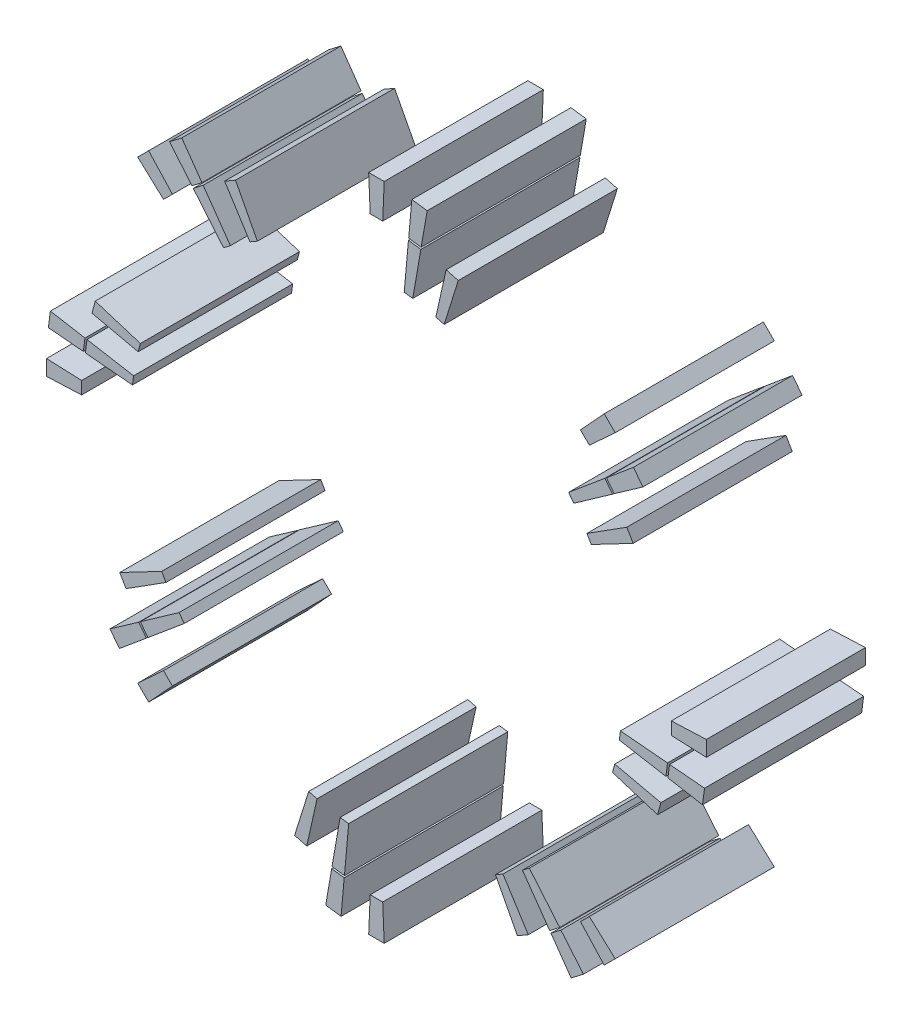
SolidWorks part; units mm, degrees
ref_plane "Спереди" through (0, 0, 0) normal (0, 0, 1) x (1, 0, 0)
ref_plane "Сверху" through (0, 0, 0) normal (0, 1, 0) x (1, 0, 0)
ref_plane "Справа" through (0, 0, 0) normal (1, 0, 0) x (0, 0, -1)
sketch "Эскиз1" plane through (0, 0, 0) normal (0, 0, 1) x (1, 0, 0)
  line L0 (55.5874, -1.1828) -> (62.2, -1.4625)
  line L1 (62.2, -1.4625) -> (62.2, 1.4625)
  line L2 (62.2, 1.4625) -> (55.5874, 1.1828)
  line L3 (55.5874, 1.1828) -> (55.5874, -1.1828)
  line L4 (40.4971, 22.4428) -> (48.396, 26.5757)
  line L5 (48.396, 26.5757) -> (47.2132, 28.6243)
  line L6 (47.2132, 28.6243) -> (39.6846, 23.8501)
  line L7 (39.6846, 23.8501) -> (40.4971, 22.4428)
  line L8 (44.8205, 32.9011) -> (50.2369, 36.7047)
  line L9 (50.2369, 36.7047) -> (48.4563, 39.0252)
  line L10 (48.4563, 39.0252) -> (43.3804, 34.7779)
  line L11 (43.3804, 34.7779) -> (44.8205, 32.9011)
  line L12 (37.2212, 27.5367) -> (44.5131, 32.6653)
  line L13 (44.5131, 32.6653) -> (43.0731, 34.542)
  line L14 (43.0731, 34.542) -> (36.232, 28.8259)
  line L15 (36.232, 28.8259) -> (37.2212, 27.5367)
  line L16 (40.1426, 38.4699) -> (45.0162, 42.9479)
  line L17 (45.0162, 42.9479) -> (42.9479, 45.0162)
  line L18 (42.9479, 45.0162) -> (38.4699, 40.1426)
  line L19 (38.4699, 40.1426) -> (40.1426, 38.4699)
  line L20 (12.7663, 44.5052) -> (15.4293, 53.013)
  line L21 (15.4293, 53.013) -> (13.1443, 53.6252)
  line L22 (13.1443, 53.6252) -> (11.1967, 44.9258)
  line L23 (11.1967, 44.9258) -> (12.7663, 44.5052)
  line L24 (8.4283, 54.9575) -> (9.5687, 61.477)
  line L25 (9.5687, 61.477) -> (6.6687, 61.8588)
  line L26 (6.6687, 61.8588) -> (6.0829, 55.2662)
  line L27 (6.0829, 55.2662) -> (8.4283, 54.9575)
  line L28 (6.848, 45.7908) -> (8.3777, 54.5734)
  line L29 (8.3777, 54.5734) -> (6.0324, 54.8821)
  line L30 (6.0324, 54.8821) -> (5.2369, 46.0029)
  line L31 (5.2369, 46.0029) -> (6.848, 45.7908)
  line L32 (1.1828, 55.5874) -> (1.4625, 62.2)
  line L33 (1.4625, 62.2) -> (-1.4625, 62.2)
  line L34 (-1.4625, 62.2) -> (-1.1828, 55.5874)
  line L35 (-1.1828, 55.5874) -> (1.1828, 55.5874)
  line L36 (-22.4428, 40.4971) -> (-26.5757, 48.396)
  line L37 (-26.5757, 48.396) -> (-28.6243, 47.2132)
  line L38 (-28.6243, 47.2132) -> (-23.8501, 39.6846)
  line L39 (-23.8501, 39.6846) -> (-22.4428, 40.4971)
  line L40 (-32.9011, 44.8205) -> (-36.7047, 50.2369)
  line L41 (-36.7047, 50.2369) -> (-39.0252, 48.4563)
  line L42 (-39.0252, 48.4563) -> (-34.7779, 43.3804)
  line L43 (-34.7779, 43.3804) -> (-32.9011, 44.8205)
  line L44 (-27.5367, 37.2212) -> (-32.6653, 44.5131)
  line L45 (-32.6653, 44.5131) -> (-34.542, 43.0731)
  line L46 (-34.542, 43.0731) -> (-28.8259, 36.232)
  line L47 (-28.8259, 36.232) -> (-27.5367, 37.2212)
  line L48 (-38.4699, 40.1426) -> (-42.9479, 45.0162)
  line L49 (-42.9479, 45.0162) -> (-45.0162, 42.9479)
  line L50 (-45.0162, 42.9479) -> (-40.1426, 38.4699)
  line L51 (-40.1426, 38.4699) -> (-38.4699, 40.1426)
  line L52 (-44.5052, 12.7663) -> (-53.013, 15.4293)
  line L53 (-53.013, 15.4293) -> (-53.6252, 13.1443)
  line L54 (-53.6252, 13.1443) -> (-44.9258, 11.1967)
  line L55 (-44.9258, 11.1967) -> (-44.5052, 12.7663)
  line L56 (-54.9575, 8.4283) -> (-61.477, 9.5687)
  line L57 (-61.477, 9.5687) -> (-61.8588, 6.6687)
  line L58 (-61.8588, 6.6687) -> (-55.2662, 6.0829)
  line L59 (-55.2662, 6.0829) -> (-54.9575, 8.4283)
  line L60 (-45.7908, 6.848) -> (-54.5734, 8.3777)
  line L61 (-54.5734, 8.3777) -> (-54.8821, 6.0324)
  line L62 (-54.8821, 6.0324) -> (-46.0029, 5.2369)
  line L63 (-46.0029, 5.2369) -> (-45.7908, 6.848)
  line L64 (-55.5874, 1.1828) -> (-62.2, 1.4625)
  line L65 (-62.2, 1.4625) -> (-62.2, -1.4625)
  line L66 (-62.2, -1.4625) -> (-55.5874, -1.1828)
  line L67 (-55.5874, -1.1828) -> (-55.5874, 1.1828)
  line L68 (-40.4971, -22.4428) -> (-48.396, -26.5757)
  line L69 (-48.396, -26.5757) -> (-47.2132, -28.6243)
  line L70 (-47.2132, -28.6243) -> (-39.6846, -23.8501)
  line L71 (-39.6846, -23.8501) -> (-40.4971, -22.4428)
  line L72 (-44.8205, -32.9011) -> (-50.2369, -36.7047)
  line L73 (-50.2369, -36.7047) -> (-48.4563, -39.0252)
  line L74 (-48.4563, -39.0252) -> (-43.3804, -34.7779)
  line L75 (-43.3804, -34.7779) -> (-44.8205, -32.9011)
  line L76 (-37.2212, -27.5367) -> (-44.5131, -32.6653)
  line L77 (-44.5131, -32.6653) -> (-43.0731, -34.542)
  line L78 (-43.0731, -34.542) -> (-36.232, -28.8259)
  line L79 (-36.232, -28.8259) -> (-37.2212, -27.5367)
  line L80 (-40.1426, -38.4699) -> (-45.0162, -42.9479)
  line L81 (-45.0162, -42.9479) -> (-42.9479, -45.0162)
  line L82 (-42.9479, -45.0162) -> (-38.4699, -40.1426)
  line L83 (-38.4699, -40.1426) -> (-40.1426, -38.4699)
  line L84 (-12.7663, -44.5052) -> (-15.4293, -53.013)
  line L85 (-15.4293, -53.013) -> (-13.1443, -53.6252)
  line L86 (-13.1443, -53.6252) -> (-11.1967, -44.9258)
  line L87 (-11.1967, -44.9258) -> (-12.7663, -44.5052)
  line L88 (-8.4283, -54.9575) -> (-9.5687, -61.477)
  line L89 (-9.5687, -61.477) -> (-6.6687, -61.8588)
  line L90 (-6.6687, -61.8588) -> (-6.0829, -55.2662)
  line L91 (-6.0829, -55.2662) -> (-8.4283, -54.9575)
  line L92 (-6.848, -45.7908) -> (-8.3777, -54.5734)
  line L93 (-8.3777, -54.5734) -> (-6.0324, -54.8821)
  line L94 (-6.0324, -54.8821) -> (-5.2369, -46.0029)
  line L95 (-5.2369, -46.0029) -> (-6.848, -45.7908)
  line L96 (-1.1828, -55.5874) -> (-1.4625, -62.2)
  line L97 (-1.4625, -62.2) -> (1.4625, -62.2)
  line L98 (1.4625, -62.2) -> (1.1828, -55.5874)
  line L99 (1.1828, -55.5874) -> (-1.1828, -55.5874)
  line L100 (22.4428, -40.4971) -> (26.5757, -48.396)
  line L101 (26.5757, -48.396) -> (28.6243, -47.2132)
  line L102 (28.6243, -47.2132) -> (23.8501, -39.6846)
  line L103 (23.8501, -39.6846) -> (22.4428, -40.4971)
  line L104 (32.9011, -44.8205) -> (36.7047, -50.2369)
  line L105 (36.7047, -50.2369) -> (39.0252, -48.4563)
  line L106 (39.0252, -48.4563) -> (34.7779, -43.3804)
  line L107 (34.7779, -43.3804) -> (32.9011, -44.8205)
  line L108 (27.5367, -37.2212) -> (32.6653, -44.5131)
  line L109 (32.6653, -44.5131) -> (34.542, -43.0731)
  line L110 (34.542, -43.0731) -> (28.8259, -36.232)
  line L111 (28.8259, -36.232) -> (27.5367, -37.2212)
  line L112 (38.4699, -40.1426) -> (42.9479, -45.0162)
  line L113 (42.9479, -45.0162) -> (45.0162, -42.9479)
  line L114 (45.0162, -42.9479) -> (40.1426, -38.4699)
  line L115 (40.1426, -38.4699) -> (38.4699, -40.1426)
  line L116 (44.5052, -12.7663) -> (53.013, -15.4293)
  line L117 (53.013, -15.4293) -> (53.6252, -13.1443)
  line L118 (53.6252, -13.1443) -> (44.9258, -11.1967)
  line L119 (44.9258, -11.1967) -> (44.5052, -12.7663)
  line L120 (54.9575, -8.4283) -> (61.477, -9.5687)
  line L121 (61.477, -9.5687) -> (61.8588, -6.6687)
  line L122 (61.8588, -6.6687) -> (55.2662, -6.0829)
  line L123 (55.2662, -6.0829) -> (54.9575, -8.4283)
  line L124 (45.7908, -6.848) -> (54.5734, -8.3777)
  line L125 (54.5734, -8.3777) -> (54.8821, -6.0324)
  line L126 (54.8821, -6.0324) -> (46.0029, -5.2369)
  line L127 (46.0029, -5.2369) -> (45.7908, -6.848)
extrude "Slot_copper_envelopes" add sketch "Эскиз1" along normal blind 30 from offset 15 separate body
